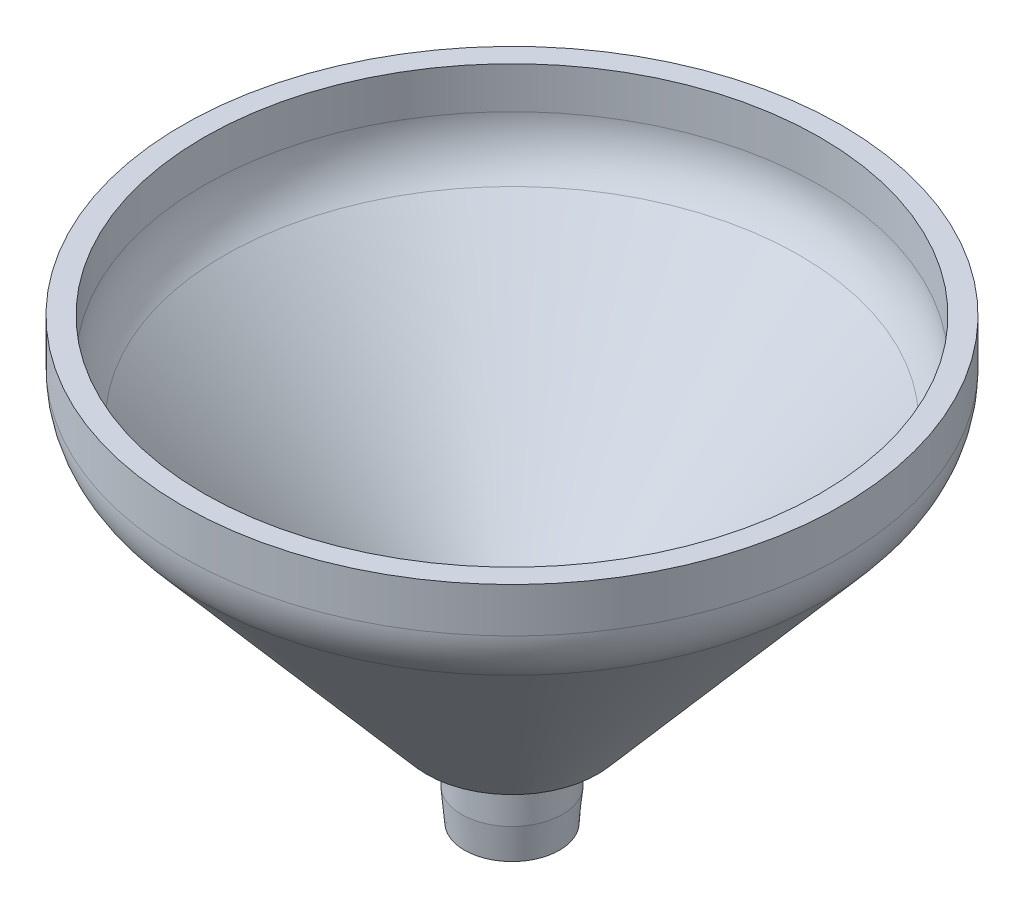
SolidWorks part; units mm, degrees
ref_plane "Front Plane" through (0, 0, 0) normal (0, 0, 1) x (1, 0, 0)
ref_plane "Top Plane" through (0, 0, 0) normal (0, 1, 0) x (1, 0, 0)
ref_plane "Right Plane" through (0, 0, 0) normal (1, 0, 0) x (0, 0, -1)
sketch "Sketch1" plane through (0, 0, 0) normal (0, 0, 1) x (1, 0, 0)
  line L0 (0, 0) -> (5.5, 0) construction
  line L1 (5.5, 0) -> (7.1, 0)
  line L2 (7.1, 0) -> (7.1, 12)
  line L3 (7.1, 12) -> (12.1, 12)
  line L4 (12.1, 12) -> (46.5, 52)
  line L6 (43.5, 52) -> (5.5, 14)
  line L7 (5.5, 14) -> (5.5, 0)
  line L8 (43.5, 52) -> (43.5, 62)
  line L9 (43.5, 62) -> (46.5, 62)
  line L10 (46.5, 62) -> (46.5, 52)
  line L11 (0, 0) -> (0, 9.6617) construction
  dimension "D1" = 7.1
  dimension "D2" = 1.6
  dimension "D3" = 5
  dimension "D4" = 135
  dimension "D5" = 40
  dimension "D6" = 12
  dimension "D7" = 3
  dimension "D8" = 2
  dimension "D9" = 10
revolve "Revolve1" add sketch "Sketch1" angle 360 about L11
fillet "Fillet1" radius 10 3 edges at (0, 14, -5.5) (0, 52, -46.5) (0, 52, -43.5)
chamfer "Chamfer1" distance 0.4 angle 85 1 edges at (0, 0, -7.1)
